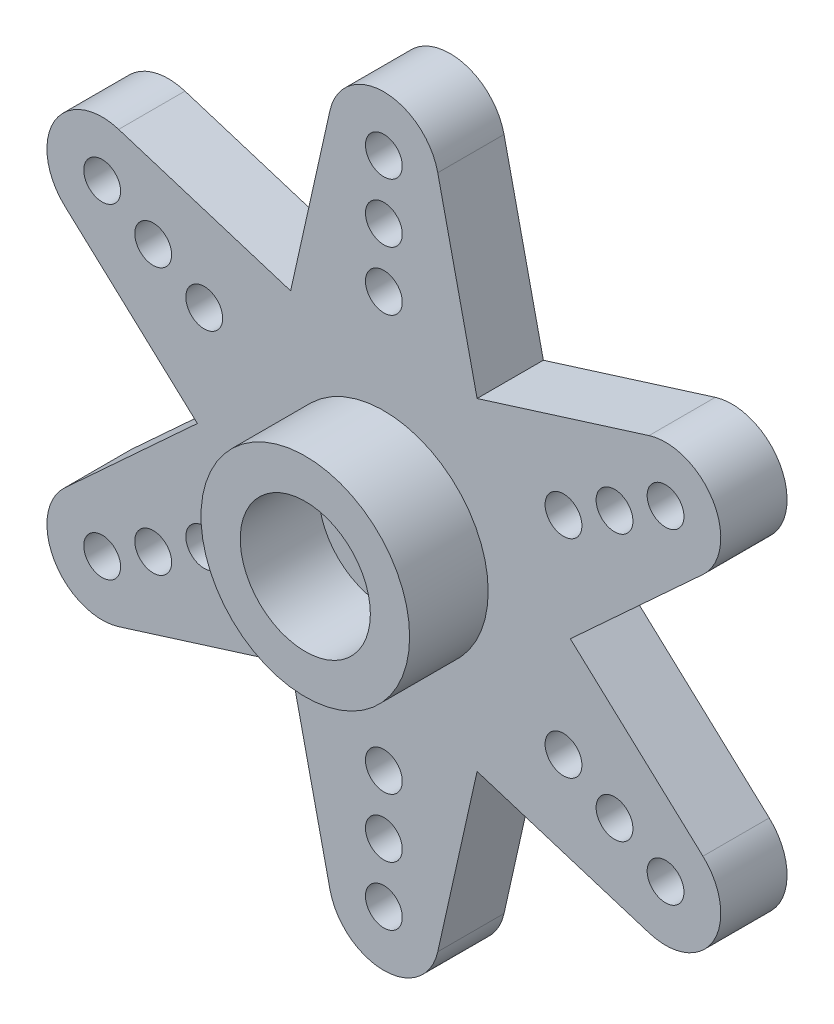
SolidWorks part; units mm, degrees
material "ABS"
ref_plane "Plano frontal" through (0, 0, 0) normal (0, 0, 1) x (1, 0, 0)
ref_plane "Plano superior" through (0, 0, 0) normal (0, 1, 0) x (1, 0, 0)
ref_plane "Plano direito" through (0, 0, 0) normal (1, 0, 0) x (0, 0, -1)
sketch "Esboço1" plane through (0, 0, 0) normal (0, 0, 1) x (1, 0, 0)
  line L0 (0, 13.25) -> (0, 0) construction
  line L1 (-2.1958, 13.7411) -> (-4.15, 5.0027)
  line L3 (2.1958, 13.7411) -> (4.15, 5.0027)
  arc A0 (-4.15, 5.0027) -> (4.15, 5.0027) centre (0, 0) ccw
  arc A1 (2.1958, 13.7411) -> (-2.1958, 13.7411) centre (0, 13.25) ccw
  circle A2 centre (0, 13.25) radius 0.75
  circle A3 centre (0, 10.85) radius 0.75
  circle A4 centre (0, 8.45) radius 0.75
  circle A6 centre (0, 0) radius 1.5
  dimension "D1" = 13
  dimension "D2" = 15.5
  dimension "D3" = 4.5
  dimension "D4" = 1.5
  dimension "D7" = 3
  dimension "D8" = 3
  dimension "D5" = 8.3
  dimension "D6" = 13.25
extrude "Ressalto-extrusão1" add sketch "Esboço1" along normal blind 2.7
pattern_circular "PadrãoCircular1" count 6 over 360 about axis through (0, 0, 0) along (0, 0, 1) of "Ressalto-extrusão1"
sketch "Esboço2" plane through (0, 0, 2.7) normal (0, 0, 1) x (1, 0, 0)
  circle A0 centre (0, 0) radius 4.25
  circle A1 centre (0, 0) radius 2.65
  dimension "D1" = 8.5
  dimension "D2" = 1.6
extrude "Ressalto-extrusão2" add sketch "Esboço2" along normal blind 3.2
sketch "Esboço3" plane through (0, 0, 0) normal (0, 0, -1) x (-1, 0, 0)
  circle A0 centre (0, 0) radius 3.35
  circle A1 centre (0, 0) radius 2.85
  dimension "D1" = 6.7
  dimension "D2" = 0.5
extrude "Ressalto-extrusão3" add sketch "Esboço3" along normal blind 0.5
